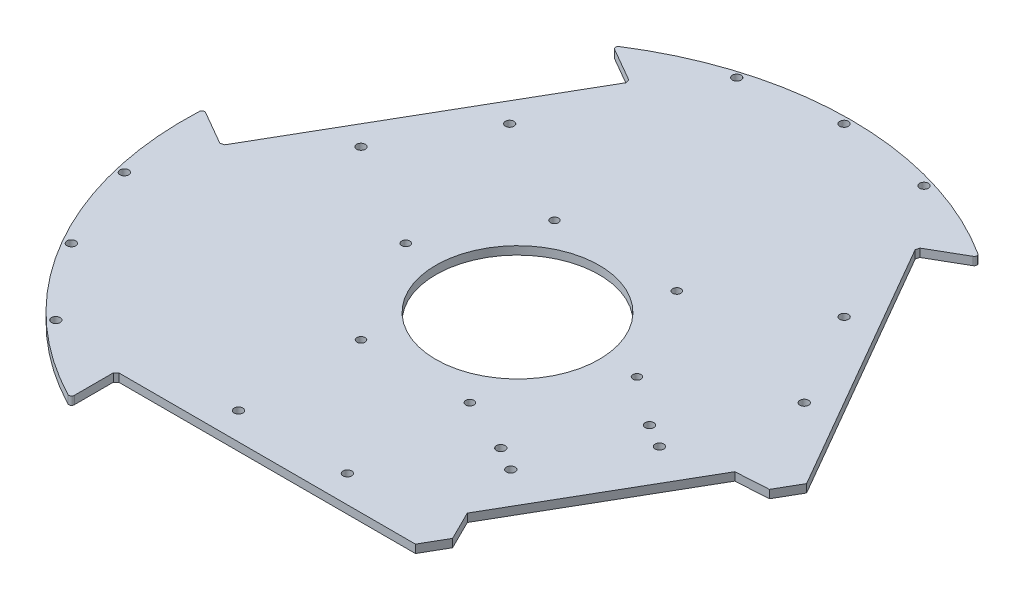
SolidWorks part; units mm, degrees
ref_plane "正面" through (0, 0, 0) normal (0, 0, 1) x (1, 0, 0)
ref_plane "平面" through (0, 0, 0) normal (0, 1, 0) x (1, 0, 0)
ref_plane "右側面" through (0, 0, 0) normal (1, 0, 0) x (0, 0, -1)
sketch "ｽｹｯﾁ1" plane through (0, 0, 0) normal (0, 1, 0) x (1, 0, 0)
  circle A0 centre (0, 0) radius 122.5
  dimension "D1" = 245
extrude "ﾎﾞｽ - 押し出し1" add sketch "ｽｹｯﾁ1" along normal blind 3
sketch "ｽｹｯﾁ2" plane through (0, 3, 0) normal (0, 1, 0) x (1, 0, 0)
  line L0 (0, 0) -> (32.476, 18.75) construction
  line L1 (-106.0881, 61.25) -> (-71.4471, 41.25) construction
  line L2 (32.476, 18.75) -> (71.4471, 41.25) construction
  line L3 (-55, -92.5) -> (55, -92.5)
  line L8 (55, -92.5) -> (55, -152.5) construction
  line L9 (55, -152.5) -> (-55, -152.5)
  line L10 (-55, -152.5) -> (-55, -92.5)
  line L11 (104.5689, 123.8814) -> (52.6073, 93.8814)
  line L12 (52.6073, 93.8814) -> (107.6073, -1.3814)
  line L13 (107.6073, -1.3814) -> (159.5689, 28.6186) construction
  line L14 (159.5689, 28.6186) -> (104.5689, 123.8814)
  line L15 (-104.5689, 123.8814) -> (-159.5689, 28.6186)
  line L16 (-159.5689, 28.6186) -> (-107.6073, -1.3814)
  line L17 (-107.6073, -1.3814) -> (-52.6073, 93.8814)
  line L18 (-52.6073, 93.8814) -> (-104.5689, 123.8814)
  line L19 (-55, -122.5) -> (55, -122.5) construction
  line L20 (133.5881, 13.6186) -> (78.5881, 108.8814) construction
  line L21 (-78.5881, 108.8814) -> (-133.5881, 13.6186) construction
  line L22 (-20, -82.5) -> (20, -82.5) construction
  line L23 (61.4471, 58.5705) -> (81.4471, 23.9295) construction
  line L24 (-81.4471, 23.9295) -> (-61.4471, 58.5705) construction
  line L25 (-71.4471, 41.25) -> (-32.476, 18.75) construction
  line L26 (71.4471, 41.25) -> (106.0881, 61.25) construction
  line L27 (0, -82.5) -> (0, -122.5) construction
  line L28 (-20, -37.5) -> (20, -37.5) construction
  line L29 (42.476, 1.4295) -> (22.476, 36.0705) construction
  line L30 (-42.476, 1.4295) -> (-22.476, 36.0705) construction
  line L31 (-32.476, 18.75) -> (0, 0) construction
  line L32 (0, 0) -> (0, -37.5) construction
  line L33 (0, -37.5) -> (0, -82.5) construction
  line L34 (-55, -109.4589) -> (0, 0) construction
  line L35 (0, 0) -> (-122.2942, 7.0981) construction
  line L36 (-119.1951, -28.2625) -> (0, 0) construction
  line L37 (0, 0) -> (-106.0881, -61.25) construction
  line L38 (-84.0736, -89.0948) -> (0, 0) construction
  line L39 (-122.2942, 7.0981) -> (-119.1951, -28.2625) construction
  line L40 (-119.1951, -28.2625) -> (-106.0881, -61.25) construction
  line L41 (-106.0881, -61.25) -> (-84.0736, -89.0948) construction
  line L42 (-84.0736, -89.0948) -> (-55, -109.4589) construction
  line L43 (0, 0) -> (0, 122.5) construction
  line L44 (-35.1215, 117.3573) -> (0, 0) construction
  line L45 (0, 0) -> (35.1215, 117.3573) construction
  line L46 (-35.1215, 117.3573) -> (0, 122.5) construction
  line L47 (0, 122.5) -> (35.1215, 117.3573) construction
  line L48 (55, -92.5) -> (60, -83.8397)
  line L49 (159.5689, 28.6186) -> (55, -152.5)
  line L50 (60, -83.8397) -> (54.6564, -73.0952)
  line L51 (54.6564, -73.0952) -> (90.6305, -10.7862)
  line L52 (90.6305, -10.7862) -> (102.6073, -10.0417)
  line L53 (72.6434, -41.9407) -> (81.3037, -46.9407) construction
  line L54 (102.6073, -10.0417) -> (107.6073, -1.3814)
  line L55 (60, -83.8397) -> (102.6073, -10.0417) construction
  line L56 (62.6434, -59.2612) -> (48.787, -51.2612) construction
  line L57 (82.6434, -24.6202) -> (68.787, -16.6202) construction
  line L58 (55.7152, -55.2612) -> (75.7152, -20.6202) construction
  line L59 (65.7152, -37.9407) -> (72.6434, -41.9407) construction
  line L60 (48.787, -51.2612) -> (40.1268, -46.2612) construction
  line L61 (68.787, -16.6202) -> (60.1268, -11.6202) construction
  circle A0 centre (0, 0) radius 122.5 construction
  circle A1 centre (20, -82.5) radius 1.6
  circle A2 centre (-20, -82.5) radius 1.6
  circle A3 centre (81.4471, 23.9295) radius 1.6
  circle A4 centre (61.4471, 58.5705) radius 1.6
  circle A5 centre (-61.4471, 58.5705) radius 1.6
  circle A6 centre (-81.4471, 23.9295) radius 1.6
  circle A7 centre (0, 0) radius 30
  circle A8 centre (-42.476, 1.4295) radius 1.5
  circle A9 centre (-22.476, 36.0705) radius 1.5
  circle A10 centre (22.476, 36.0705) radius 1.5
  circle A11 centre (42.476, 1.4295) radius 1.5
  circle A12 centre (20, -37.5) radius 1.5
  circle A13 centre (-20, -37.5) radius 1.5
  circle A14 centre (0, 0) radius 120 construction
  circle A15 centre (-116.7626, -27.6857) radius 1.6
  circle A16 centre (-103.923, -60) radius 1.6
  circle A17 centre (-82.3578, -87.2765) radius 1.6
  circle A18 centre (0, 120) radius 1.6
  circle A23 centre (-34.4048, 114.9622) radius 1.6
  circle A24 centre (34.4048, 114.9622) radius 1.6
  circle A25 centre (48.787, -51.2612) radius 1.6
  circle A26 centre (68.787, -16.6202) radius 1.6
  circle A27 centre (40.1268, -46.2612) radius 1.6
  circle A28 centre (60.1268, -11.6202) radius 1.6
  point P32 (0, -82.5)
  point P33 (-55, -122.5)
  point P35 (133.5881, 13.6186)
  point P37 (-133.5881, 13.6186)
  point P38 (71.4471, 41.25)
  point P41 (-71.4471, 41.25)
  point P50 (0, -37.5)
  point P53 (32.476, 18.75)
  point P56 (-32.476, 18.75)
  point P106 (66.4471, -52.7406)
  point P107 (0, 0)
  dimension "D5" = 3.2
  dimension "D7" = 60
  dimension "D9" = 3
  dimension "D10" = 240
  dimension "D11" = 3.2
  dimension "D19" = 3.2
  dimension "D1" = 120
  dimension "D2" = 110
  dimension "D3" = 30
  dimension "D4" = 40
  dimension "D6" = 40
  dimension "D8" = 45
  dimension "D12" = 10
  dimension "D13" = 10
  dimension "D14" = 10
  dimension "D15" = 12
  dimension "D16" = 40
  dimension "D17" = 16
  dimension "D18" = 10
extrude "ｶｯﾄ - 押し出し1" cut sketch "ｽｹｯﾁ2" against normal through all
chamfer "面取り1" distance 1 angle 45 4 edges at (-55, 1.5, 92.5) (-107.6073, 1.5, 1.3814) (-52.6073, 1.5, -93.8814) (52.6073, 1.5, -93.8814)
fillet "ﾌｨﾚｯﾄ1" radius 1 4 edges at (-55, 1.5, 109.4589) (-122.2942, 1.5, -7.0981) (-67.2942, 1.5, -102.3608) (67.2942, 1.5, -102.3608)
sketch "ｽｹｯﾁ3" [suppressed] plane through (0, 0, 0) normal (0, 1, 0) x (1, 0, 0)
  line L0 (55.4808, -108.6798) -> (0, 0) construction
  line L1 (0, 0) -> (121.8598, 6.2921) construction
  arc A0 (55, -107.8251) -> (56.4609, -108.7125) centre (56, -107.8251) ccw construction
  arc A1 (122.3783, 5.4597) -> (120.8793, 6.2811) centre (121.3793, 5.4151) ccw construction
  dimension "D1" = 65.912
